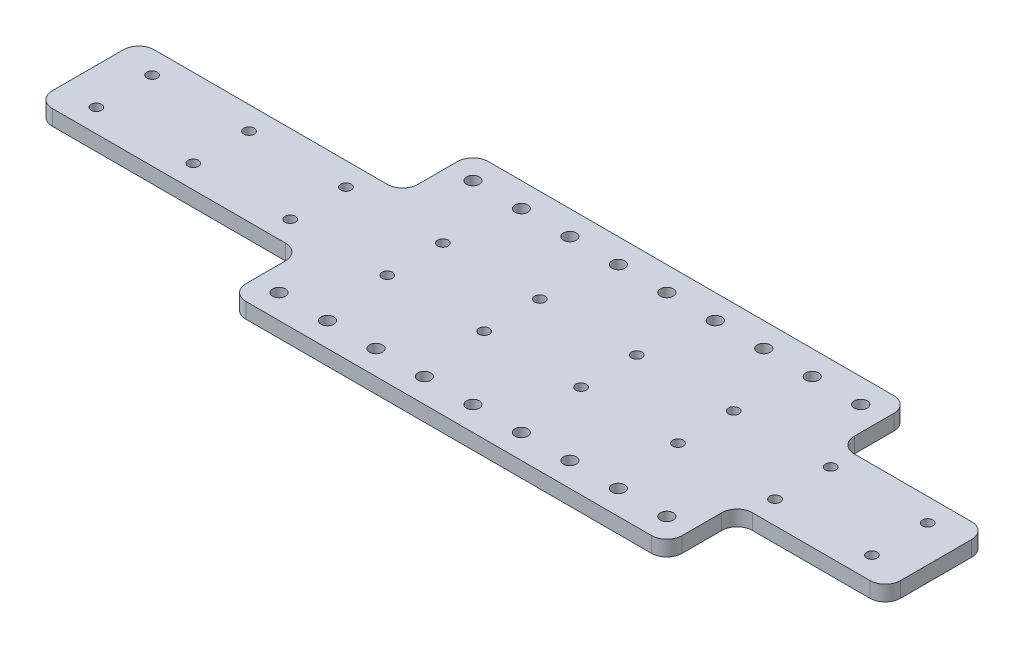
SolidWorks part; units mm, degrees
material "Acrylic (Medium-high impact)"
ref_plane "Front Plane" through (0, 0, 0) normal (0, 0, 1) x (1, 0, 0)
ref_plane "Top Plane" through (0, 0, 0) normal (0, 1, 0) x (1, 0, 0)
ref_plane "Right Plane" through (0, 0, 0) normal (1, 0, 0) x (0, 0, -1)
sketch "Sketch7" plane through (0, 0, 0) normal (0, 1, 0) x (1, 0, 0)
  line L0 (-175, 0) -> (175, 0) construction
  line L3 (175, -21) -> (-175, -21)
  line L5 (175, 21) -> (-175, 21)
  line L6 (-175, -21) -> (-175, 21)
  line L11 (175, 21) -> (175, -21)
  dimension "D1" = 42
  dimension "D2" = 350
extrude "Boss-Extrude3" add sketch "Sketch7" against normal blind 6.35
sketch "Sketch2" plane through (0, 0, 0) normal (0, 1, 0) x (1, 0, 0)
  line L0 (0, 0) -> (175, 0) construction
  line L1 (175, -21) -> (175, 21) construction
  line L5 (160, 11.5) -> (160, 0) construction
  circle A0 centre (120, 11.5) radius 2.15
  circle A1 centre (120, -11.5) radius 2.15
  circle A2 centre (80, 11.5) radius 2.15
  circle A3 centre (160, 11.5) radius 2.15
  circle A4 centre (80, -11.5) radius 2.15
  circle A5 centre (160, -11.5) radius 2.15
  circle A6 centre (40, 11.5) radius 2.15
  circle A7 centre (40, -11.5) radius 2.15
  circle A8 centre (0, 11.5) radius 2.15
  circle A9 centre (0, -11.5) radius 2.15
  circle A10 centre (-40, 11.5) radius 2.15
  circle A11 centre (-40, -11.5) radius 2.15
  circle A12 centre (-80, 11.5) radius 2.15
  circle A13 centre (-80, -11.5) radius 2.15
  circle A14 centre (-120, 11.5) radius 2.15
  circle A15 centre (-120, -11.5) radius 2.15
  circle A16 centre (-160, 11.5) radius 2.15
  circle A17 centre (-160, -11.5) radius 2.15
  dimension "D1" = 11.5
  dimension "D2" = 9
  dimension "D3" = 40
  dimension "D4" = 4.3
  dimension "D5" = 15
extrude "Cut-Extrude1" cut sketch "Sketch2" against normal through all
sketch "Sketch1" plane through (0, 0, 0) normal (0, 1, 0) x (1, 0, 0)
  line L0 (23.8744, 49.9993) -> (23.8744, 0) construction
  line L1 (-66.1256, -50.0007) -> (113.8744, -50.0007)
  line L2 (-66.1256, -50.0007) -> (-66.1256, -21)
  line L3 (-66.1256, 49.9993) -> (113.8744, 49.9993)
  line L4 (113.8744, -50.0007) -> (113.8744, -21)
  line L5 (-66.1256, 21) -> (113.8744, 21)
  line L6 (175, 21) -> (-175, 21) construction
  line L7 (-66.1256, -21) -> (113.8744, -21)
  line L8 (-175, -21) -> (175, -21) construction
  line L9 (23.8744, 0) -> (23.8744, -50.0007) construction
  line L10 (-66.1256, 0) -> (113.8744, 0) construction
  line L11 (-66.1256, 21) -> (-66.1256, 49.9993)
  line L12 (113.8744, 21) -> (113.8744, 49.9993)
  line L13 (-66.1256, 21) -> (-66.1256, -21) construction
  line L14 (113.8744, 21) -> (113.8744, -21) construction
  dimension "D1" = 100
  dimension "D2" = 180
extrude "Boss-Extrude4" add sketch "Sketch1" against normal through all
sketch "Sketch3" plane through (0, 0, 0) normal (0, 1, 0) x (1, 0, 0)
  line L0 (23.8744, 49.9993) -> (23.8744, -50.0007) construction
  line L1 (-66.1256, -50.0007) -> (113.8744, -50.0007) construction
  line L3 (23.8744, 39.9993) -> (43.8744, 39.9993) construction
  line L4 (23.8744, -0.0007) -> (123.8706, -0.0007) construction
  line L9 (113.8744, 49.9993) -> (-66.1256, 49.9993) construction
  circle A0 centre (23.8744, 39.9993) radius 2.65
  circle A1 centre (43.8744, 39.9993) radius 2.65
  circle A2 centre (63.8744, 39.9993) radius 2.65
  circle A3 centre (103.8744, 39.9993) radius 2.65
  circle A6 centre (-36.1256, 39.9993) radius 2.65
  circle A7 centre (83.8744, 39.9993) radius 2.65
  circle A10 centre (-56.1256, 39.9993) radius 2.65
  circle A11 centre (-16.1256, 39.9993) radius 2.65
  circle A12 centre (3.8744, 39.9993) radius 2.65
  circle A13 centre (3.8744, -40.0007) radius 2.65
  circle A14 centre (-16.1256, -40.0007) radius 2.65
  circle A15 centre (-56.1256, -40.0007) radius 2.65
  circle A18 centre (83.8744, -40.0007) radius 2.65
  circle A19 centre (-36.1256, -40.0007) radius 2.65
  circle A22 centre (103.8744, -40.0007) radius 2.65
  circle A23 centre (63.8744, -40.0007) radius 2.65
  circle A24 centre (43.8744, -40.0007) radius 2.65
  circle A25 centre (23.8744, -40.0007) radius 2.65
  dimension "D1" = 5.3
  dimension "D2" = 10
  dimension "D4" = 20
  dimension "D5" = 10
  dimension "D3" = 5
extrude "Cut-Extrude2" cut sketch "Sketch3" against normal through all
fillet "Fillet2" radius 6.35 12 edges at (113.8744, -3.175, 50.0007) (113.8744, -3.175, -49.9993) (-66.1256, -3.175, -49.9993) (-175, -3.175, -21) (-175, -3.175, 21) (-66.1256, -3.175, 50.0007) (175, -3.175, 21) (175, -3.175, -21)
